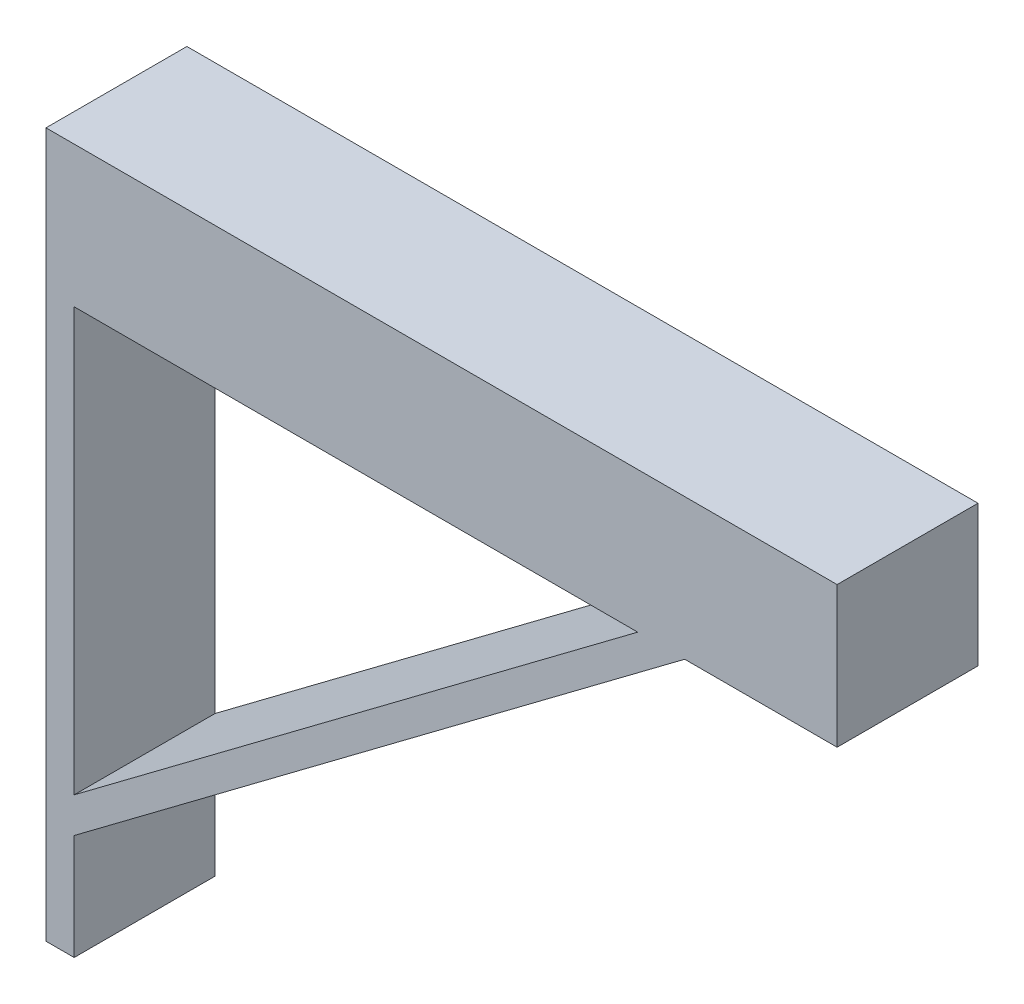
SolidWorks part; units mm, degrees
ref_plane "Front Plane" through (0, 0, 0) normal (0, 0, 1) x (1, 0, 0)
ref_plane "Top Plane" through (0, 0, 0) normal (0, 1, 0) x (1, 0, 0)
ref_plane "Right Plane" through (0, 0, 0) normal (1, 0, 0) x (0, 0, -1)
sketch "Sketch1" plane through (0, 0, 0) normal (0, 0, 1) x (1, 0, 0)
  line L0 (-43.956, -46.4835) -> (36.044, 13.5165)
  line L1 (-47.956, 33.5165) -> (-43.956, 33.5165)
  line L2 (-47.956, 33.5165) -> (-47.956, -66.4835)
  line L3 (-47.956, -66.4835) -> (-43.956, -66.4835)
  line L4 (-43.956, 13.5165) -> (-43.956, -46.4835)
  line L5 (-43.956, 33.5165) -> (64.344, 33.5165)
  line L6 (-43.956, 33.5165) -> (-43.956, 13.5165)
  line L7 (-43.956, 13.5165) -> (36.044, 13.5165)
  line L8 (64.344, 33.5165) -> (64.344, 13.5165)
  line L9 (42.7106, 13.5165) -> (-43.956, -51.4835)
  line L10 (-43.956, -51.4835) -> (-43.956, -66.4835)
  line L11 (42.7106, 13.5165) -> (64.344, 13.5165)
  dimension "D1" = 100
  dimension "D2" = 108.3
  dimension "D3" = 60
  dimension "D4" = 20
  dimension "D5" = 4
  dimension "D6" = 4
  dimension "D7" = 80
extrude "Boss-Extrude1" add sketch "Sketch1" along normal blind 20
